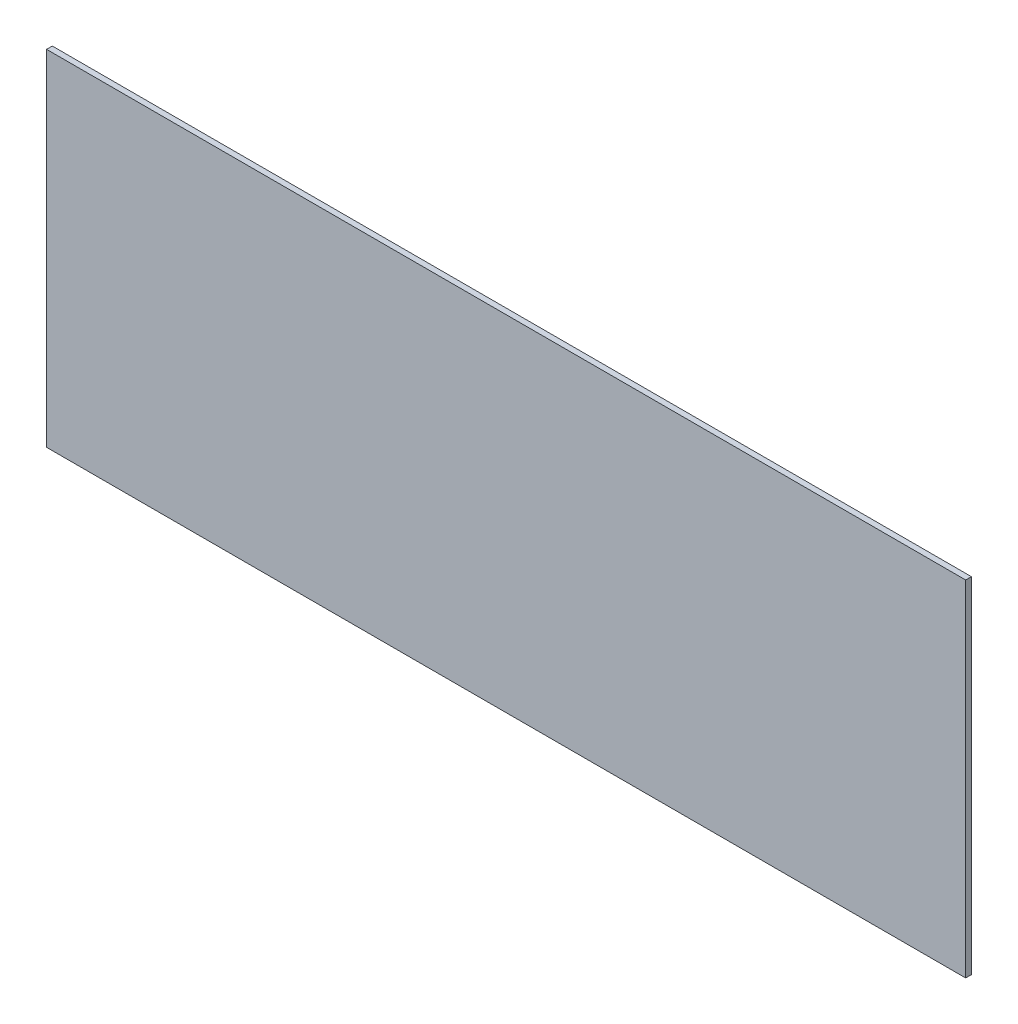
SolidWorks part; units mm, degrees
ref_plane "Front Plane" through (0, 0, 0) normal (0, 0, 1) x (1, 0, 0)
ref_plane "Top Plane" through (0, 0, 0) normal (0, 1, 0) x (1, 0, 0)
ref_plane "Right Plane" through (0, 0, 0) normal (1, 0, 0) x (0, 0, -1)
sketch "Sketch1" plane through (0, 0, 0) normal (0, 0, 1) x (1, 0, 0)
  line L1 (0, 0) -> (406.4, 0)
  line L2 (0, 0) -> (0, 152.4)
  line L3 (0, 152.4) -> (406.4, 152.4)
  line L4 (406.4, 0) -> (406.4, 152.4)
extrude "Boss-Extrude1" add sketch "Sketch1" along normal blind 2.54
